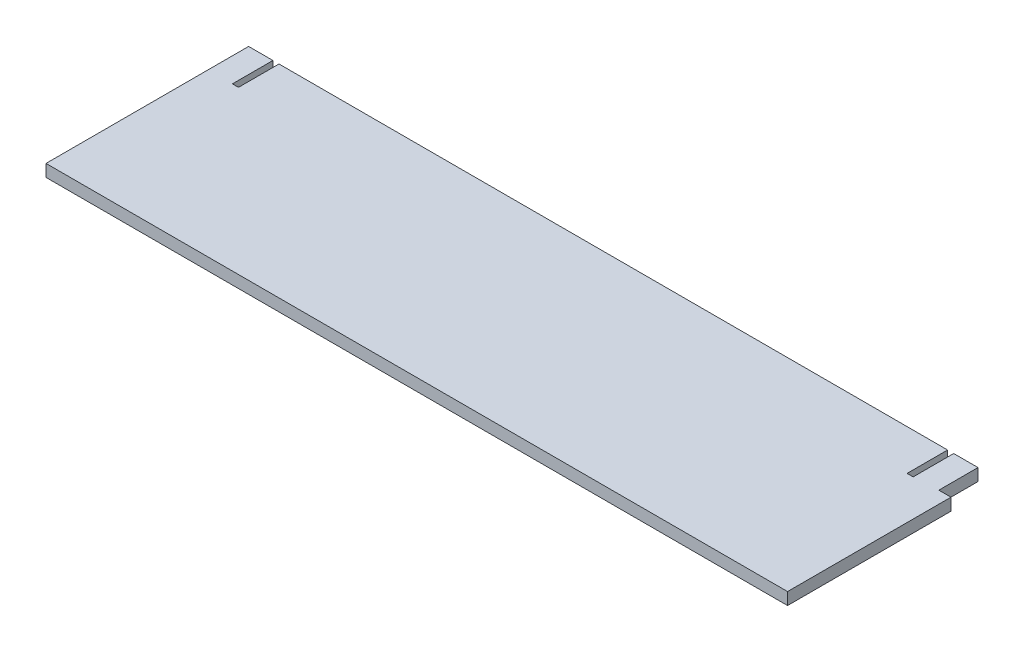
SolidWorks part; units mm, degrees
ref_plane "Front Plane" through (0, 0, 0) normal (0, 0, 1) x (1, 0, 0)
ref_plane "Top Plane" through (0, 0, 0) normal (0, 1, 0) x (1, 0, 0)
ref_plane "Right Plane" through (0, 0, 0) normal (1, 0, 0) x (0, 0, -1)
sketch "Sketch1" plane through (0, 0, 0) normal (0, 1, 0) x (1, 0, 0)
  line L0 (-84, 25) -> (-84, 15)
  line L1 (-90, -25) -> (90, -25)
  line L2 (-90, -25) -> (-90, 25)
  line L3 (-90, 25) -> (-84, 25)
  line L4 (90, -25) -> (90, 25)
  line L5 (-84, 15) -> (-82.5, 15)
  line L6 (-82.5, 15) -> (-82.5, 25)
  line L7 (82.5, 25) -> (82.5, 15)
  line L8 (82.5, 15) -> (84, 15)
  line L9 (84, 15) -> (84, 25)
  line L10 (-82.5, 25) -> (82.5, 25)
  line L11 (84, 25) -> (90, 25)
  point P4 (-90, 0)
  point P5 (0, 25)
  dimension "D1" = 50
  dimension "D2" = 180
  dimension "D3" = 6
  dimension "D4" = 1.5
  dimension "D5" = 10
extrude "Boss-Extrude1" add sketch "Sketch1" along normal mid plane 3
sketch "Sketch2" plane through (0, 0, 0) normal (0, 1, 0) x (1, 0, 0)
  line L0 (90, -25) -> (90, 25) construction
  line L1 (90, 15.3314) -> (93, 15.3314)
  line L2 (90, 15.3314) -> (90, -25)
  line L3 (90, -25) -> (93, -25)
  line L4 (93, 15.3314) -> (93, -25)
  line L5 (-90, -25) -> (90, -25) construction
  dimension "D1" = 3
extrude "Boss-Extrude2" add sketch "Sketch2" along normal mid plane 3
equation "\"mdfWidth\"= 3"
equation "\"cellSide\"= 180"
equation "\"mazeHeight\"= 50"
equation "\"slitHeight\"= 10"
equation "\"slitWidth\"= \"wallThickness\""
equation "\"gripWidth\"= 6"
equation "\"wallThickness\"= 1.5"
equation "\"D1@Sketch1\"= \"mazeHeight\""
equation "\"D2@Sketch1\"= \"cellSide\""
equation "\"D3@Sketch1\"= \"gripWidth\""
equation "\"D4@Sketch1\"= \"wallThickness\""
equation "\"D5@Sketch1\"= \"slitHeight\""
equation "\"D1@Boss-Extrude1\"= \"mdfWidth\""
equation "\"D1@Sketch2\"= \"mdfWidth\""
equation "\"D1@Boss-Extrude2\"= \"mdfWidth\""
